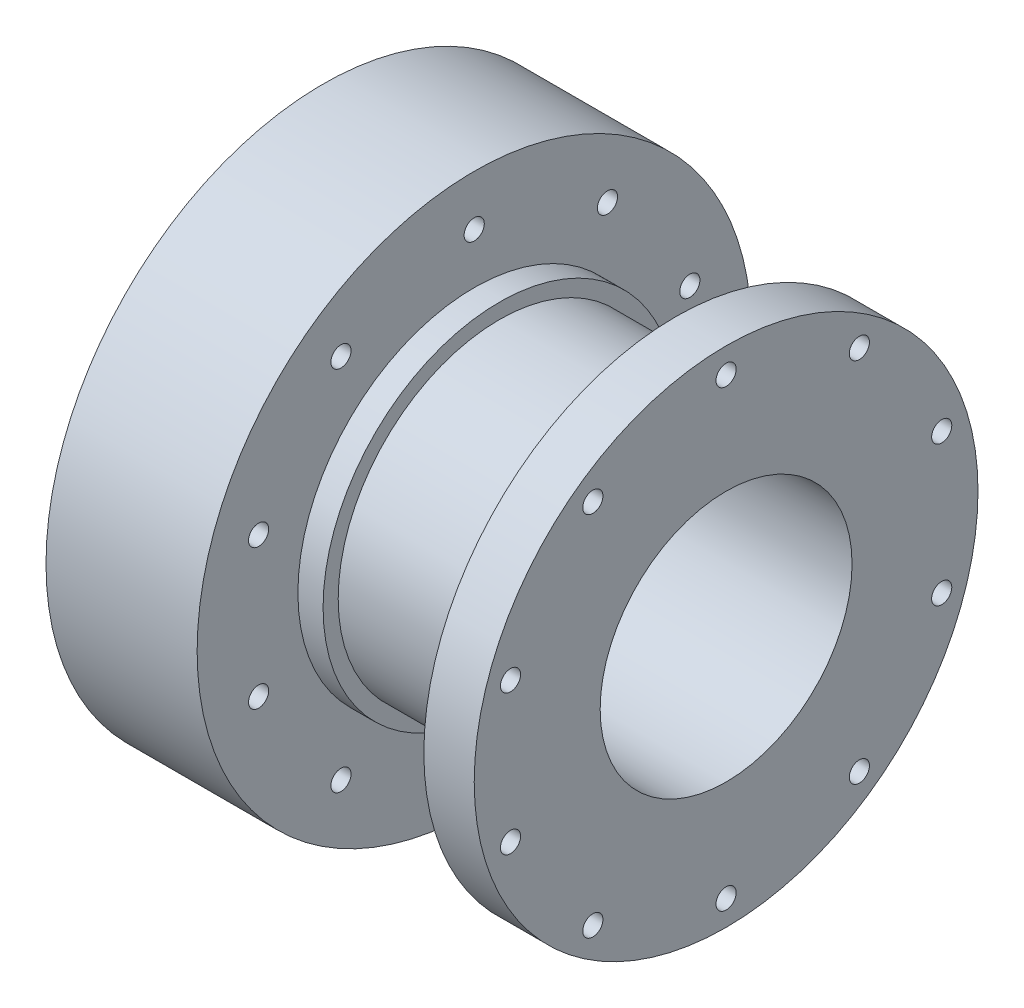
SolidWorks part; units mm, degrees
ref_plane "Front Plane" through (0, 0, 0) normal (0, 0, 1) x (1, 0, 0)
ref_plane "Top Plane" through (0, 0, 0) normal (0, 1, 0) x (1, 0, 0)
ref_plane "Right Plane" through (0, 0, 0) normal (1, 0, 0) x (0, 0, -1)
sketch "Sketch1" plane through (0, 0, 0) normal (0, 0, 1) x (1, 0, 0)
  line L0 (-41.889, 0) -> (72.6128, 0) construction
  line L1 (72.6128, 25) -> (72.6128, 50)
  line L2 (72.6128, 50) -> (62.6128, 50)
  line L3 (62.6128, 50) -> (62.6128, 35)
  line L4 (62.6128, 35) -> (57.6128, 35)
  line L5 (57.6128, 35) -> (57.6128, 32)
  line L6 (57.6128, 32) -> (27.6128, 32)
  line L7 (27.6128, 32) -> (27.6128, 35)
  line L8 (27.6128, 35) -> (22.6128, 35)
  line L9 (22.6128, 35) -> (22.6128, 55)
  line L10 (22.6128, 55) -> (-7.3872, 55)
  line L11 (-7.3872, 55) -> (-7.3872, 50)
  line L12 (-7.3872, 50) -> (12.6128, 50)
  line L13 (12.6128, 50) -> (12.6128, 40)
  line L14 (12.6128, 40) -> (-7.3872, 40)
  line L15 (-7.3872, 40) -> (-7.3872, 35)
  line L16 (-7.3872, 35) -> (12.6128, 35)
  line L17 (12.6128, 35) -> (12.6128, 25)
  line L18 (12.6128, 25) -> (72.6128, 25)
  dimension "D1" = 10
  dimension "D2" = 30
  dimension "D3" = 40
  dimension "D4" = 5
  dimension "D5" = 7
  dimension "D6" = 5
  dimension "D7" = 5
  dimension "D8" = 10
  dimension "D9" = 25
  dimension "D10" = 80
  dimension "D11" = 35
  dimension "D12" = 3
  dimension "D13" = 50
  dimension "D14" = 60
  dimension "D15" = 20
revolve "Revolve1" add sketch "Sketch1" angle 360 about L0
sketch "Sketch2" plane through (72.6128, 0, 0) normal (1, 0, 0) x (0, 0, -1)
  circle A0 centre (0, 45) radius 2
  circle A1 centre (26.4503, 36.4058) radius 2
  circle A2 centre (42.7975, 13.9058) radius 2
  circle A3 centre (42.7975, -13.9058) radius 2
  circle A4 centre (26.4503, -36.4058) radius 2
  circle A5 centre (0, -45) radius 2
  circle A6 centre (-26.4503, -36.4058) radius 2
  circle A7 centre (-42.7975, -13.9058) radius 2
  circle A8 centre (-42.7975, 13.9058) radius 2
  circle A9 centre (-26.4503, 36.4058) radius 2
  point P23 (0, 0)
  dimension "D2" = 4
  dimension "D1" = 45
  dimension "D3" = 10
extrude "Cut-Extrude1" cut sketch "Sketch2" against normal through all
